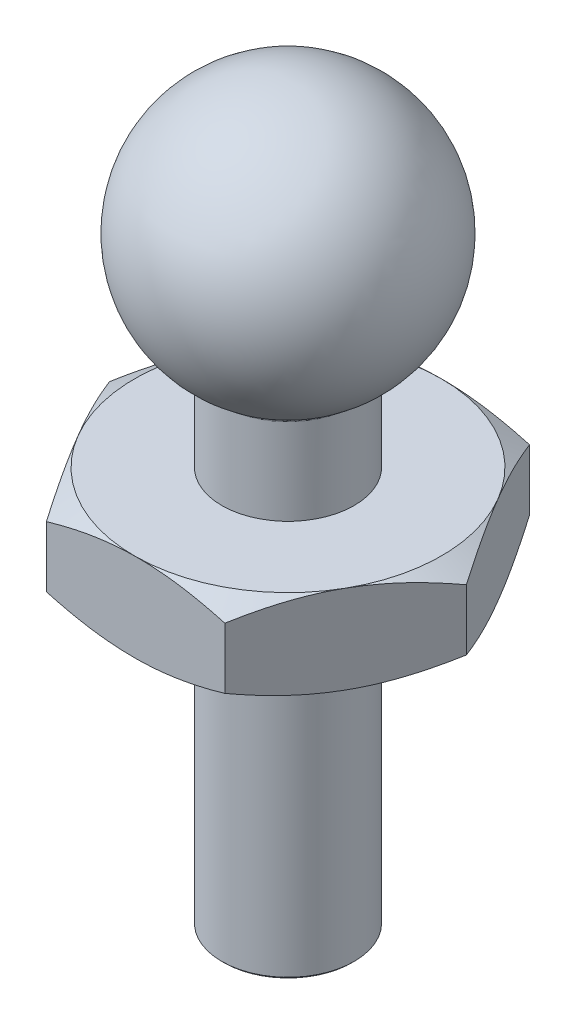
SolidWorks part; units mm, degrees
ref_plane "Front Plane" through (0, 0, 0) normal (0, 0, 1) x (1, 0, 0)
ref_plane "Top Plane" through (0, 0, 0) normal (0, 1, 0) x (1, 0, 0)
ref_plane "Right Plane" through (0, 0, 0) normal (1, 0, 0) x (0, 0, -1)
sketch "Sketch1" plane through (0, 0, 0) normal (0, 0, 1) x (1, 0, 0)
  line L0 (0, 16.5981) -> (0, 0)
  line L1 (0, 0) -> (1.5, 0)
  line L2 (1.5, 0) -> (1.5, 11)
  arc A0 (1.5, 11) -> (0, 16.5981) centre (0, 13.5981) ccw construction
  arc A1 (1.5, 11) -> (0, 16.5981) centre (0, 13.5981) ccw
  dimension "D1" = 6
  dimension "D2" = 1.5
  dimension "D3" = 11
revolve "Revolve1" add sketch "Sketch1" angle 360 about L0
sketch "Sketch3" plane through (0, 0, 0) normal (0, 0, 1) x (1, 0, 0)
  line L0 (-6.7491, 7) -> (6.7491, 7)
  line L1 (-1.5, 0) -> (1.5, 0) construction
  point P2 (0, 7)
  dimension "D1" = 7
split line "Split Line2"
chamfer "Chamfer1" distance 0.05 1 edges at (0, 0, 1.5)
ref_plane "Plane1" through (0, 7, 0) normal (0, -1, 0) x (-1, 0, 0)
sketch "Sketch4" plane through (0, 7, 0) normal (0, -1, 0) x (-1, 0, 0)
  line L1 (1.9838, -3.4921) -> (4.0162, -0.028)
  line L2 (4.0162, -0.028) -> (2.0323, 3.4641)
  line L3 (2.0323, 3.4641) -> (-1.9838, 3.4921)
  line L4 (-1.9838, 3.4921) -> (-4.0162, 0.028)
  line L5 (-4.0162, 0.028) -> (-2.0323, -3.4641)
  line L6 (-2.0323, -3.4641) -> (1.9838, -3.4921)
  circle A0 centre (0, 0) radius 1.5
  circle A1 centre (0, 0) radius 3.4782 construction
  circle A2 centre (0, 0) radius 1.5 construction
  dimension "D1" = 6
extrude "Boss-Extrude1" add sketch "Sketch4" against normal blind 2
sketch "Sketch5" plane through (0, 7, 0) normal (0, -1, 0) x (1, 0, 0)
  circle A0 centre (0, 0) radius 3.4782
extrude "Cut-Extrude2" cut sketch "Sketch5" against normal blind 2 draft 60 flip side to cut
sketch "Sketch6" plane through (0, 9, 0) normal (0, 1, 0) x (1, 0, 0)
  circle A0 centre (0, 0) radius 3.4782
extrude "Cut-Extrude3" cut sketch "Sketch6" against normal blind 2 draft 60 flip side to cut
fillet "Fillet1" radius 0.075 1 edges at (0, 11, 1.5)
